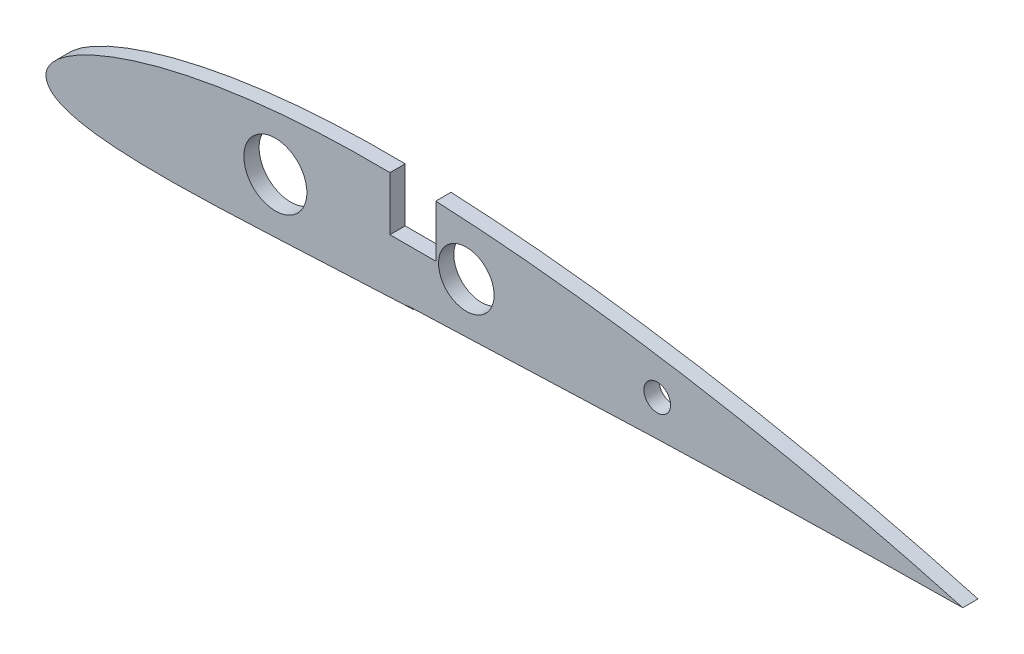
SolidWorks part; units mm, degrees
ref_plane "前视基准面" through (0, 0, 0) normal (0, 0, 1) x (1, 0, 0)
ref_plane "上视基准面" through (0, 0, 0) normal (0, 1, 0) x (1, 0, 0)
ref_plane "右视基准面" through (0, 0, 0) normal (1, 0, 0) x (0, 0, -1)
sketch "草图1" plane through (0, 0, 0) normal (0, 0, 1) x (1, 0, 0)
  spline S0 degree 3 poles (240, 0) (238.175, 0.5039) (234.5527, 1.504) (229.1447, 2.9367) (223.8081, 4.3083) (218.5409, 5.6171) (213.3432, 6.8665) (208.2143, 8.0584) (203.1537, 9.1947) (198.1611, 10.2773) (193.236, 11.308) (188.3781, 12.2882) (183.587, 13.2195) (178.8624, 14.1033) (174.2038, 14.9409) (169.6111, 15.7335) (165.0838, 16.4823) (160.6216, 17.1884) (156.2243, 17.8528) (151.8915, 18.4765) (147.623, 19.0605) (143.4184, 19.6055) (139.2776, 20.1126) (135.2002, 20.5824) (131.1859, 21.0158) (127.2346, 21.4136) (123.346, 21.7766) (119.5197, 22.1053) (115.7557, 22.4007) (112.0536, 22.6634) (108.4132, 22.8942) (104.8344, 23.0931) (101.3169, 23.2635) (98.9918, 23.353) (97.8397, 23.3974) knots 0 0 0 0 0.039337 0.078079 0.116237 0.153822 0.190842 0.227308 0.263226 0.298605 0.333451 0.367771 0.401572 0.43486 0.467639 0.499916 0.531695 0.562982 0.593781 0.624097 0.653933 0.683295 0.712186 0.740611 0.768573 0.796076 0.823123 0.849719 0.875867 0.90157 0.926832 0.951655 0.976043 1 1 1 1
  spline S1 degree 3 poles (97.8397, 23.3974) (97.227, 23.449) (96.6142, 23.5007) (95.9998, 23.5195) (95.9996, 23.5195) (95.9991, 23.5195) (95.9982, 23.5195) (95.9965, 23.5196) (95.993, 23.5197) (95.9859, 23.52) (95.9719, 23.5205) (95.9437, 23.5215) (95.8875, 23.5236) (95.7751, 23.5276) (95.5505, 23.5356) (95.1022, 23.5511) (94.2096, 23.5804) (92.4398, 23.6317) (89.9361, 23.6857) (86.967, 23.7199) (84.0456, 23.7242) (81.172, 23.6997) (78.3467, 23.6471) (75.5698, 23.5673) (72.8415, 23.4614) (70.162, 23.3301) (67.5316, 23.1745) (64.9504, 22.9953) (62.4187, 22.7934) (59.9366, 22.5698) (57.5043, 22.3254) (55.1218, 22.0609) (52.7894, 21.7773) (50.5072, 21.4755) (48.2753, 21.1563) (46.0937, 20.8205) (43.9627, 20.469) (41.8822, 20.1027) (39.8523, 19.7223) (37.8732, 19.3288) (35.9448, 18.9228) (34.0671, 18.5052) (32.2403, 18.0768) (30.4643, 17.6384) (28.7391, 17.1908) (27.0648, 16.7346) (25.4412, 16.2706) (23.8685, 15.7996) (22.3466, 15.3223) (20.8754, 14.8394) (19.4549, 14.3515) (18.0851, 13.8593) (16.7658, 13.3635) (15.4971, 12.8648) (14.2788, 12.3636) (13.111, 11.8606) (11.9934, 11.3564) (10.9261, 10.8516) (9.9088, 10.3467) (8.9416, 9.8421) (8.0244, 9.3385) (7.1569, 8.8362) (6.3392, 8.3358) (5.5711, 7.8376) (4.8524, 7.342) (4.1831, 6.8495) (3.5631, 6.3604) (2.9922, 5.875) (2.4702, 5.3936) (1.9971, 4.9164) (1.5728, 4.4438) (1.197, 3.9759) (0.8698, 3.5129) (0.591, 3.0548) (0.3605, 2.6019) (0.1783, 2.1542) (0.0444, 1.7117) (-0.0413, 1.2746) (-0.0778, 0.8432) (-0.0693, 0.4168) (-0.023, 0.1387) (0, 0) knots 0 0 0 0 0.017583 0.017585 0.017587 0.01759 0.017597 0.017612 0.01764 0.017698 0.017813 0.018043 0.018503 0.019423 0.021262 0.024934 0.032256 0.046814 0.075587 0.103904 0.131765 0.159169 0.186118 0.212611 0.23865 0.264233 0.289362 0.314037 0.338257 0.362024 0.385337 0.408197 0.430604 0.452558 0.474059 0.495108 0.515706 0.535852 0.555546 0.57479 0.593584 0.611927 0.629821 0.647266 0.664263 0.680813 0.696915 0.712571 0.727781 0.742548 0.756871 0.770751 0.784191 0.797191 0.809752 0.821878 0.833569 0.844828 0.855657 0.866058 0.876036 0.885593 0.894734 0.903462 0.911784 0.919705 0.927232 0.934374 0.94114 0.947541 0.953591 0.959304 0.964701 0.969801 0.974633 0.979225 0.983613 0.987838 0.991944 0.995981 1 1 1 1
  spline S2 degree 3 poles (0, 0) (0.0321, -0.1369) (0.0964, -0.4113) (0.2523, -0.8082) (0.4511, -1.1926) (0.697, -1.5636) (0.9884, -1.9213) (1.3255, -2.2659) (1.7078, -2.5975) (2.1354, -2.9161) (2.6079, -3.222) (3.1254, -3.5152) (3.6878, -3.7957) (4.2948, -4.0638) (4.9465, -4.3195) (5.6427, -4.5627) (6.3833, -4.7937) (7.1683, -5.0124) (7.9975, -5.219) (8.8709, -5.4135) (9.7883, -5.5959) (10.7496, -5.7664) (11.7548, -5.925) (12.8037, -6.0719) (13.8963, -6.207) (15.0325, -6.3306) (16.2122, -6.4426) (17.4352, -6.5434) (18.7016, -6.6328) (20.0113, -6.7112) (21.3642, -6.7786) (22.7602, -6.8351) (24.1993, -6.881) (25.6814, -6.9164) (27.2065, -6.9415) (28.7745, -6.9565) (30.3855, -6.9616) (32.0394, -6.9569) (33.7363, -6.9429) (35.476, -6.9196) (37.2587, -6.8873) (39.0842, -6.8464) (40.9528, -6.7972) (42.8644, -6.7398) (44.819, -6.6748) (46.8167, -6.6023) (48.8576, -6.5228) (50.9418, -6.4367) (53.0694, -6.3444) (55.2404, -6.2462) (57.455, -6.1427) (59.7132, -6.0343) (62.0154, -5.9214) (64.3615, -5.8047) (66.7517, -5.6846) (69.1863, -5.5617) (71.6654, -5.4366) (74.1892, -5.3099) (76.7578, -5.1821) (79.3717, -5.054) (82.0308, -4.9263) (84.7355, -4.7995) (87.4861, -4.6745) (90.2828, -4.5521) (92.6423, -4.4531) (94.311, -4.3858) (95.1529, -4.3525) (95.5758, -4.336) (95.7878, -4.3277) (95.8938, -4.3236) (95.9469, -4.3215) (95.9735, -4.3205) (95.9867, -4.32) (95.9934, -4.3197) (95.9967, -4.3196) (95.9983, -4.3195) (95.9992, -4.3195) (95.9996, -4.3195) (95.9998, -4.3195) (96.6143, -4.2997) (95.3872, -4.2485) (94.1603, -4.1974) knots 0 0 0 0 0.004212 0.008443 0.012745 0.017169 0.021761 0.026561 0.031604 0.036921 0.042537 0.048473 0.054747 0.061373 0.068365 0.075731 0.083482 0.091624 0.100162 0.109103 0.11845 0.128207 0.138377 0.148962 0.159965 0.171387 0.18323 0.195495 0.208184 0.221297 0.234836 0.2488 0.26319 0.278008 0.293253 0.308927 0.325028 0.341559 0.358519 0.375909 0.39373 0.411981 0.430664 0.449778 0.469325 0.489306 0.50972 0.530569 0.551854 0.573575 0.595733 0.618331 0.641368 0.664846 0.688766 0.71313 0.73794 0.763196 0.788902 0.815057 0.841666 0.868729 0.896248 0.924227 0.952668 0.967062 0.974302 0.977934 0.979752 0.980662 0.981117 0.981345 0.981458 0.981515 0.981544 0.981558 0.981565 0.981569 0.98157 0.981572 1 1 1 1
  spline S3 degree 3 poles (94.1603, -4.1974) (95.3539, -4.1552) (97.763, -4.0701) (101.4092, -3.9363) (105.1208, -3.7973) (108.8974, -3.6531) (112.739, -3.5046) (116.6453, -3.3523) (120.616, -3.1969) (124.651, -3.039) (128.7499, -2.8793) (132.9126, -2.7184) (137.1387, -2.557) (141.4281, -2.3957) (145.7804, -2.2353) (150.1954, -2.0764) (154.6728, -1.9195) (159.2123, -1.7654) (163.8136, -1.6146) (168.4764, -1.4677) (173.2004, -1.3251) (177.9853, -1.1875) (182.8307, -1.0551) (187.7363, -0.9285) (192.7019, -0.8078) (197.7269, -0.6934) (202.811, -0.5853) (207.9538, -0.4837) (213.155, -0.3886) (218.414, -0.2996) (223.7303, -0.2167) (229.1035, -0.1394) (234.5331, -0.0669) (238.1715, -0.0224) (240, 0) knots 0 0 0 0 0.024557 0.049564 0.07502 0.100924 0.127273 0.154067 0.181303 0.208979 0.237094 0.265645 0.294632 0.324052 0.353902 0.384182 0.414888 0.446019 0.477572 0.509547 0.541939 0.574748 0.60797 0.641604 0.675647 0.710097 0.744951 0.780206 0.81586 0.85191 0.888352 0.925184 0.962401 1 1 1 1
extrude "凸台-拉伸1" add sketch "草图1" along normal blind 4
sketch "草图2" plane through (0, 0, 0) normal (0, 0, 1) x (1, 0, 0)
  circle A0 centre (60, 8.25) radius 8.2578
extrude "切除-拉伸1" cut sketch "草图2" along normal through all
sketch "草图3" plane through (0, 0, 0) normal (0, 0, 1) x (1, 0, 0)
  circle A0 centre (110, 9.5093) radius 7.2758
extrude "切除-拉伸2" cut sketch "草图3" along normal through all
sketch "草图4" plane through (0, 0, 0) normal (0, 0, 1) x (1, 0, 0)
  circle A0 centre (160, 7.7037) radius 3.4931
extrude "切除-拉伸3" cut sketch "草图4" along normal through all
sketch "草图5" plane through (0, 0, 0) normal (0, 0, 1) x (1, 0, 0)
  line L0 (90, 9.6) -> (102, 9.6)
  line L1 (102, 9.6) -> (102, 30)
  line L2 (102, 30) -> (90, 30)
  line L3 (90, 30) -> (90, 9.6)
extrude "切除-拉伸4" cut sketch "草图5" along normal through all
